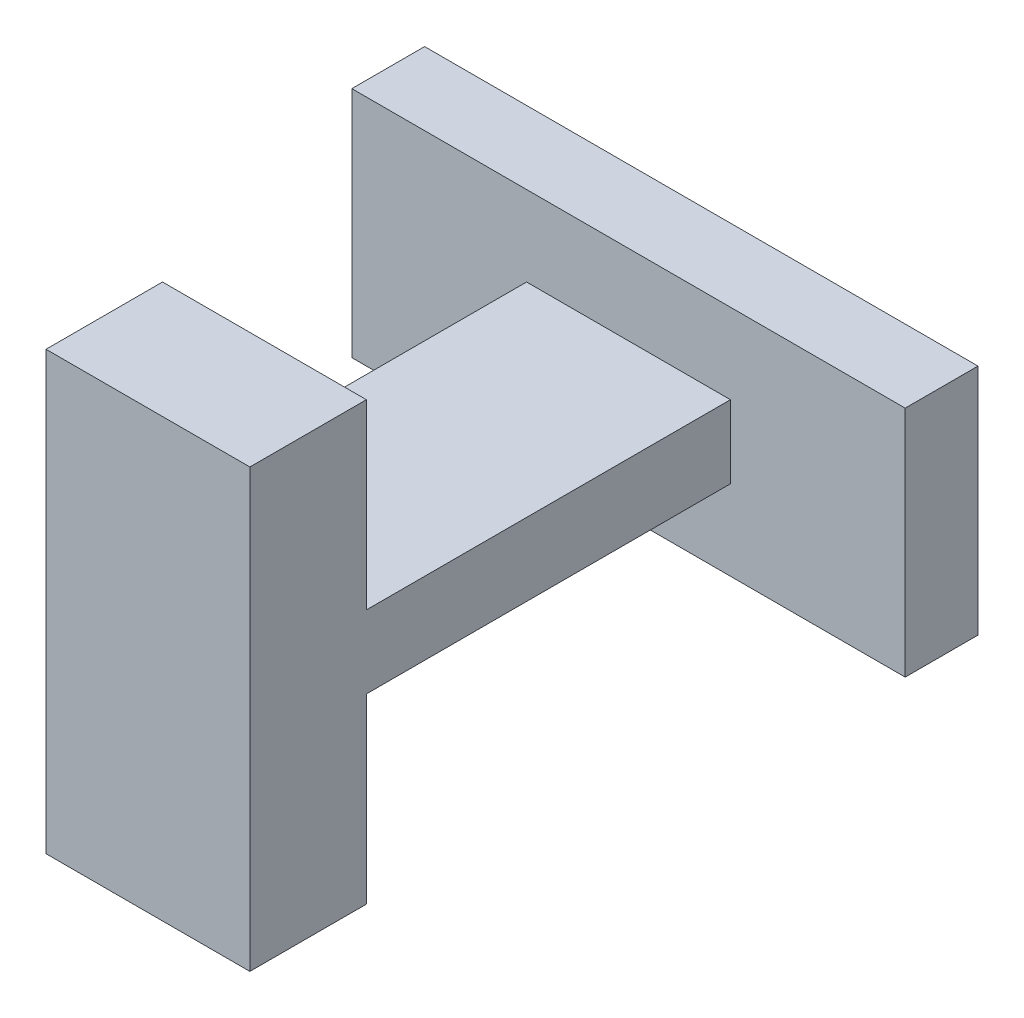
SolidWorks part; units mm, degrees
ref_plane "前视基准面" through (0, 0, 0) normal (0, 0, 1) x (1, 0, 0)
ref_plane "上视基准面" through (0, 0, 0) normal (0, 1, 0) x (1, 0, 0)
ref_plane "右视基准面" through (0, 0, 0) normal (1, 0, 0) x (0, 0, -1)
sketch "草图1" plane through (0, 0, 0) normal (0, 0, 1) x (1, 0, 0)
  line L1 (-19, -8) -> (19, -8)
  line L2 (-19, -8) -> (-19, 8)
  line L3 (-19, 8) -> (19, 8)
  line L4 (19, -8) -> (19, 8)
  line L5 (-19, -8) -> (19, 8) construction
  line L6 (-19, 8) -> (19, -8) construction
  point P0 (0, 0)
  dimension "D1" = 38
  dimension "D2" = 16
extrude "凸台-拉伸1" add sketch "草图1" along normal blind 5
sketch "草图2" plane through (0, 0, 5) normal (0, 0, 1) x (1, 0, 0)
  line L1 (-7, -2.5) -> (7, -2.5)
  line L2 (-7, -2.5) -> (-7, 2.5)
  line L3 (-7, 2.5) -> (7, 2.5)
  line L4 (7, -2.5) -> (7, 2.5)
  line L5 (-7, -2.5) -> (7, 2.5) construction
  line L6 (-7, 2.5) -> (7, -2.5) construction
  point P0 (0, 0)
  dimension "D1" = 5
  dimension "D2" = 14
extrude "凸台-拉伸2" add sketch "草图2" along normal blind 25
sketch "草图3" plane through (0, 0, 30) normal (0, 0, 1) x (1, 0, 0)
  line L1 (-7, -15) -> (7, -15)
  line L2 (-7, -15) -> (-7, 15)
  line L3 (-7, 15) -> (7, 15)
  line L4 (7, -15) -> (7, 15)
  line L5 (-7, -15) -> (7, 15) construction
  line L6 (-7, 15) -> (7, -15) construction
  point P0 (0, 0)
  dimension "D1" = 14
  dimension "D2" = 30
extrude "凸台-拉伸3" add sketch "草图3" along normal blind 8
